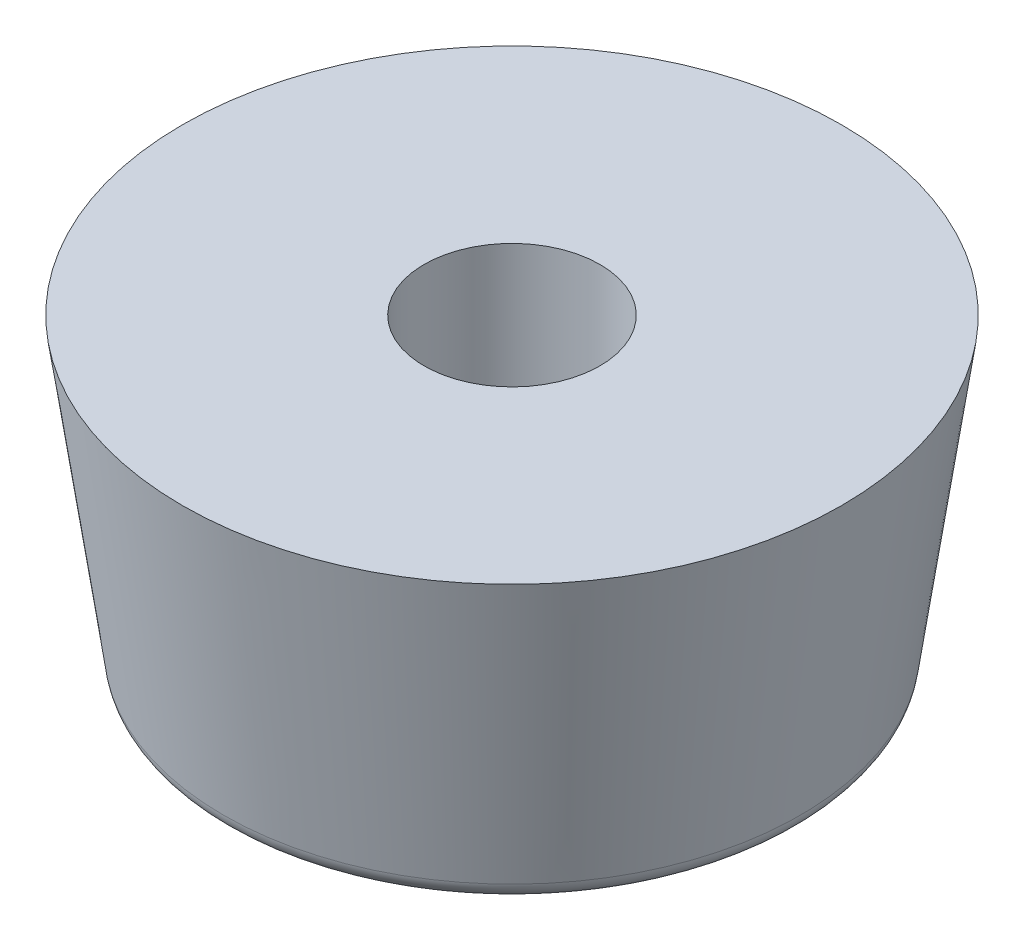
SolidWorks part; units mm, degrees
ref_plane "Front" through (0, 0, 0) normal (0, 0, 1) x (1, 0, 0)
ref_plane "Top" through (0, 0, 0) normal (0, 1, 0) x (1, 0, 0)
ref_plane "Right" through (0, 0, 0) normal (1, 0, 0) x (0, 0, -1)
sketch "草图1" plane through (0, 0, 0) normal (0, 0, 1) x (1, 0, 0)
  line L0 (2, 7) -> (7.5, 7)
  line L1 (7.5, 7) -> (6.5, 0)
  line L2 (6.5, 0) -> (3.5, 0)
  line L3 (3.5, 0) -> (3.5, 3.27)
  line L4 (3.5, 3.27) -> (2, 3.27)
  line L5 (2, 7) -> (2, 3.27)
  line L8 (0, 0) -> (0, 6.4196) construction
  dimension "D1" = 2
  dimension "D2" = 6.5
  dimension "D3" = 7.5
  dimension "D4" = 7
  dimension "D5" = 3.5
  dimension "D6" = 3.27
revolve "旋转1" add sketch "草图1" angle 360 about L8
fillet "圆角2" radius 0.5 2 edges at (0, 0, -3.5) (0, 0, -6.5)
